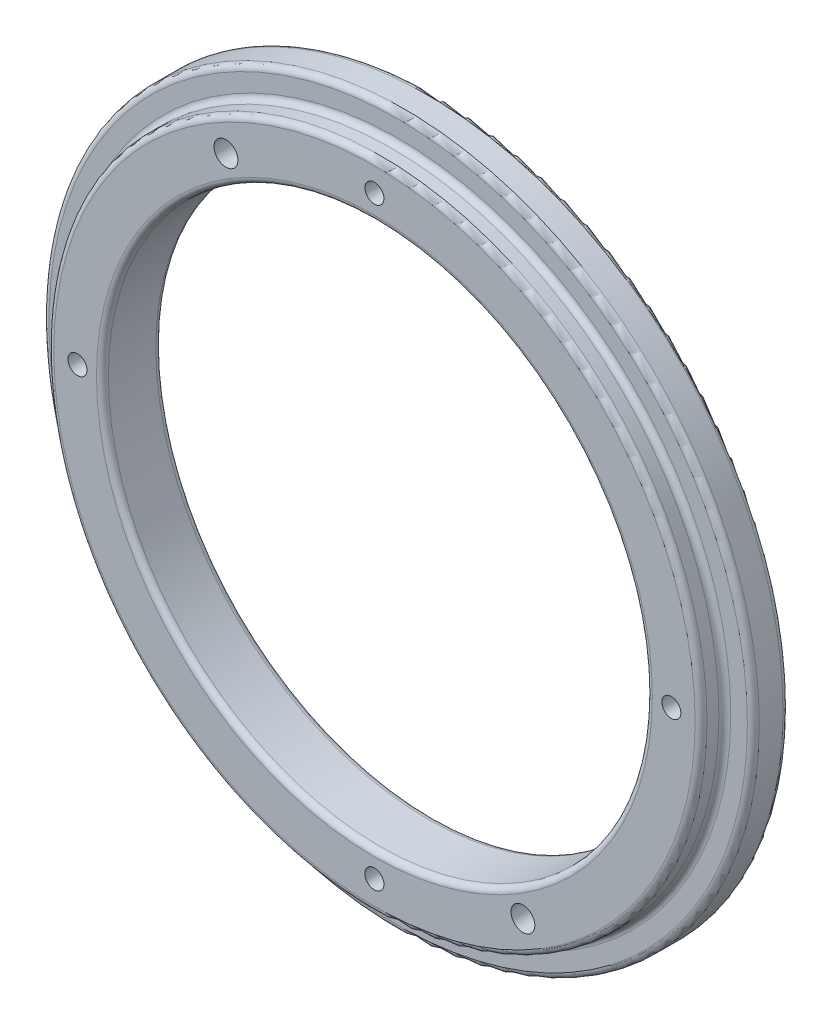
SolidWorks part; units mm, degrees
material "6061 Alloy"
ref_plane "Front Plane" through (0, 0, 0) normal (0, 0, 1) x (1, 0, 0)
ref_plane "Top Plane" through (0, 0, 0) normal (0, 1, 0) x (1, 0, 0)
ref_plane "Right Plane" through (0, 0, 0) normal (1, 0, 0) x (0, 0, -1)
sketch "Sketch1" plane through (0, 0, 0) normal (0, 0, 1) x (1, 0, 0)
  circle A0 centre (0, 0) radius 75.946
  circle A1 centre (0, 0) radius 58.166
  dimension "D1" = 151.892
  dimension "D2" = 116.332
extrude "Boss-Extrude1" add sketch "Sketch1" along normal blind 7.62
sketch "Sketch2" plane through (0, 0, 7.62) normal (0, 0, 1) x (1, 0, 0)
  circle A0 centre (0, 0) radius 69.85
  circle A2 centre (0, 0) radius 58.166 construction
  circle A3 centre (0, 0) radius 58.166
  dimension "D1" = 139.7
extrude "Boss-Extrude2" add sketch "Sketch2" along normal blind 5.08
sketch "Sketch4" plane through (0, 0, 0) normal (0, 0, -1) x (-1, 0, 0)
  line L0 (0, 0) -> (0, 63.5) construction
  circle A0 centre (0, 63.5) radius 2.032
  circle A1 centre (63.5, 0) radius 2.032
  circle A2 centre (0, -63.5) radius 2.032
  circle A3 centre (-63.5, 0) radius 2.032
  point P14 (0, 0)
  dimension "D1" = 63.5
  dimension "D2" = 4.064
  dimension "D3" = 4
extrude "Cut-Extrude1" cut sketch "Sketch4" against normal through all
fillet "Fillet1" radius 1.27 6 edges at (58.166, 0, 12.7) (58.166, 0, 0) (69.85, 0, 7.62) (69.85, 0, 12.7) (75.946, 0, 7.62) (75.946, 0, 0)
sketch "Sketch5" plane through (0, 0, 0) normal (0, 0, -1) x (-1, 0, 0)
  line L0 (-37.973, -65.7712) -> (37.973, 65.7712) construction
  line L1 (0, 0) -> (-75.946, 0) construction
  circle A0 centre (0, 0) radius 75.946 construction
  circle A1 centre (-31.75, -54.9926) radius 2.5527
  circle A2 centre (31.75, 54.9926) radius 2.5527
  point P4 (0, 0)
  dimension "D2" = 63.5
  dimension "D4" = 5.1054
  dimension "D1" = 120
  dimension "D3" = 63.5
extrude "Cut-Extrude2" cut sketch "Sketch5" against normal through all
